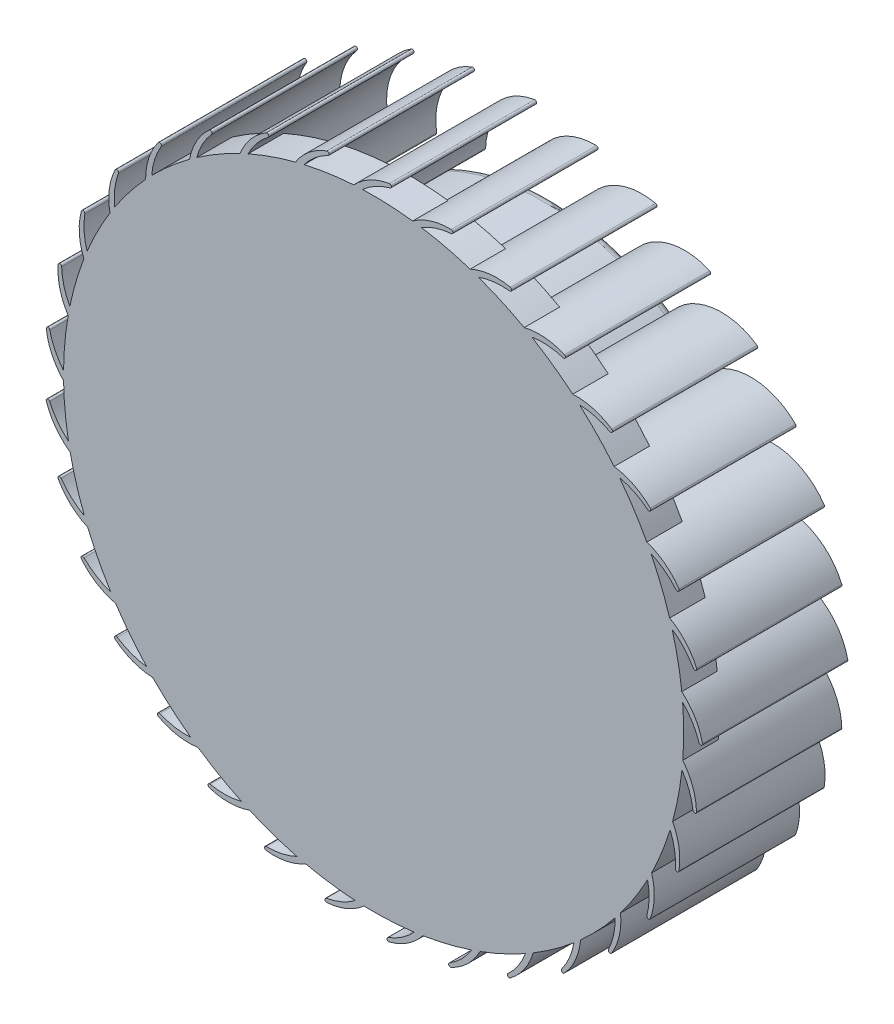
SolidWorks part; units mm, degrees
ref_plane "Płaszczyzna przednia" through (0, 0, 0) normal (0, 0, 1) x (1, 0, 0)
ref_plane "Płaszczyzna górna" through (0, 0, 0) normal (0, 1, 0) x (1, 0, 0)
ref_plane "Płaszczyzna prawa" through (0, 0, 0) normal (1, 0, 0) x (0, 0, -1)
sketch "Sketch1" plane through (0, 0, 0) normal (0, 1, 0) x (1, 0, 0)
  line L0 (0, 0) -> (0, 8.7082) construction
  line L1 (0, 0) -> (17.5, 0)
  line L2 (17.5, 0) -> (17.5, 2)
  line L3 (17.5, 2) -> (12.5, 3.5)
  line L4 (12.5, 3.5) -> (12.5, 10)
  line L5 (12.5, 10) -> (0, 10)
  line L6 (0, 10) -> (0, 0)
  dimension "D1" = 17.5
  dimension "D2" = 2
  dimension "D3" = 10
  dimension "D4" = 5
  dimension "D5" = 6.5
revolve "Revolve1" add sketch "Sketch1" angle 360 about L0
ref_plane "Plane1" through (18.5, 0, 0) normal (1, 0, 0) x (0, 0, -1)
ref_plane "Plane2" through (0, 0, -8.2) normal (0, 0, -1) x (-1, 0, 0)
sketch "Sketch3" plane through (0, 0, -8.2) normal (0, 0, -1) x (-1, 0, 0)
  arc A0 (-18.5, 1.9516) -> (-12.5, 4.6949) centre (-14.9505, 2.1215) cw
  arc A1 (-18.5, 1.9516) -> (-12.5, 4.6949) centre (-14.701, 1.5758) cw
  circle A2 centre (0, 0) radius 12.5 construction
  point P1 (-12.2726, 3.6602)
  point P3 (0, 0)
  point P7 (0, 0)
  point P8 (-17.1001, 2.832)
  point P9 (-17.0632, 2.832)
  point P11 (-14, 4.6949)
  dimension "D1" = 0.6
  dimension "12,5" = 12.5
  dimension "D3" = 18.5
extrude "Boss-Extrude1" add sketch "Sketch3" against normal up to surface (8.2 mm away) up to face at (17.5, 0, 0)
fillet "Fillet1" radius 0.1 2 edges at (12.5, 4.6949, -5.7221) (18.5, 1.9516, -4.1)
pattern_circular "CirPattern1" count 33 over 360 about axis through (0, 0, 0) along (0, 0, 1) of "Boss-Extrude1", "Fillet1"
fillet "Fillet2" radius 0.5 1 edges at (12.5, 0, -10)
